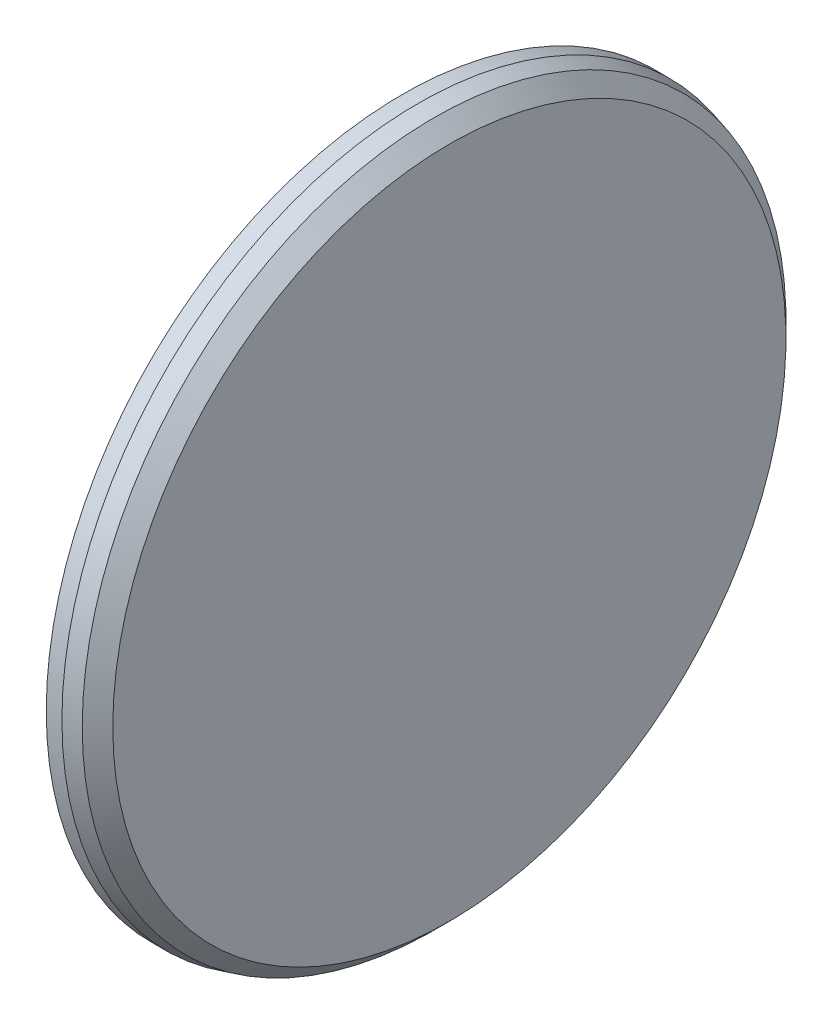
SolidWorks part; units mm, degrees
material "Alliage 1060"
ref_plane "Plan de face" through (0, 0, 0) normal (0, 0, 1) x (1, 0, 0)
ref_plane "Plan de dessus" through (0, 0, 0) normal (0, 1, 0) x (1, 0, 0)
ref_plane "Plan de droite" through (0, 0, 0) normal (1, 0, 0) x (0, 0, -1)
sketch "Esquisse1" plane through (0, 0, 0) normal (0, 0, 1) x (1, 0, 0)
  line L0 (0, 0) -> (0, 430)
  line L1 (0, 430) -> (-19.5096, 449.5096)
  line L2 (-19.5096, 449.5096) -> (-40, 455)
  line L3 (-40, 455) -> (-60, 455)
  line L4 (-60, 455) -> (-60, 410)
  line L5 (-60, 410) -> (-30, 410)
  line L6 (-30, 410) -> (-30, 100)
  line L7 (-30, 100) -> (-80, 100)
  line L8 (-80, 100) -> (-80, 0)
  line L9 (-80, 0) -> (0, 0)
  line L10 (0, 430) -> (79.5834, 350.4166) construction
  line L11 (-19.5096, 449.5096) -> (83.7655, 421.8371) construction
  line L12 (-40, 455) -> (62.7356, 455) construction
  dimension "D1" = 100
  dimension "D2" = 30
  dimension "D3" = 455
  dimension "D4" = 430
  dimension "D5" = 80
  dimension "D6" = 45
  dimension "D7" = 15
  dimension "D8" = 20
  dimension "D9" = 45
  dimension "D10" = 60
revolve "Révolution1" add sketch "Esquisse1" angle 360 about L9
sketch "Esquisse2" plane through (-30, 0, 0) normal (-1, 0, 0) x (0, 0, 1)
  line L0 (-20, 104.6122) -> (-20, 350.5901)
  line L1 (20, 103.4821) -> (20, 399.9655)
  line L2 (0, 0) -> (0, 462.1645) construction
  circle A0 centre (0, 0) radius 410 construction
  circle A1 centre (0, 0) radius 100 construction
  arc A2 (26.0892, 409.1691) -> (-57.0212, 406.0155) centre (0, 0) ccw
  arc A3 (21.9395, 97.5636) -> (-23.2124, 97.2686) centre (0, 0) ccw
  arc A4 (-57.0212, 406.0155) -> (-20, 350.5901) centre (-80, 350.5901) cw
  arc A5 (-23.2124, 97.2686) -> (-20, 104.6122) centre (-30, 104.6122) ccw
  arc A6 (20, 103.4821) -> (21.9395, 97.5636) centre (30, 103.4821) ccw
  arc A7 (26.0892, 409.1691) -> (20, 399.9655) centre (30, 399.9655) ccw
  point P13 (0, 0)
  point P16 (0, 0)
  point P21 (20, 407.4934)
  dimension "D3" = 10
  dimension "D4" = 10
  dimension "D5" = 60
  dimension "D6" = 10
  dimension "D1" = 40
  dimension "D2" = 20
extrude "Boss.-Extru.1" add sketch "Esquisse2" along normal offset from surface (20 mm away) 10 up to face at (-60, 0, 410)
pattern_circular "Répétition circulaire1" count 9 over 360 about axis through (0, 0, 0) along (1, 0, 0) of "Boss.-Extru.1"
equation "\"A\"= 60"
equation "\"B\"= 910"
equation "\"D3@Esquisse1\"=\"B\"/2"
equation "\"D4@Esquisse1\"=(\"B\"-50)/2"
equation "\"D5@Esquisse1\"=\"A\"+20"
equation "\"D10@Esquisse1\"=\"A\""
